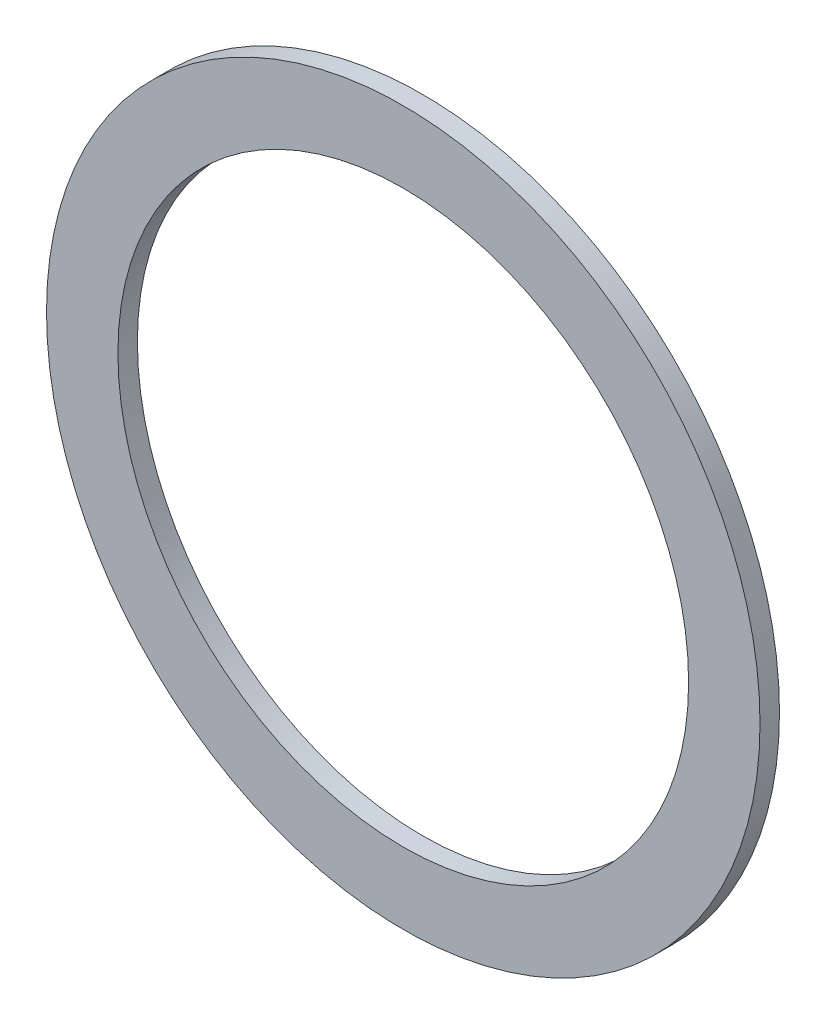
SolidWorks part; units mm, degrees
material "6061-T6 (SS)"
ref_plane "Front" through (0, 0, 0) normal (0, 0, 1) x (1, 0, 0)
ref_plane "Top" through (0, 0, 0) normal (0, 1, 0) x (1, 0, 0)
ref_plane "Right" through (0, 0, 0) normal (1, 0, 0) x (0, 0, -1)
sketch "Sketch1" plane through (0, 0, 0) normal (0, 0, 1) x (1, 0, 0)
  circle A0 centre (0, 0) radius 27.9146
  circle A1 centre (0, 0) radius 34.8996
  dimension "D1" = 69.7992
  dimension "D2" = 6.985
extrude "Boss-Extrude1" add sketch "Sketch1" along normal blind 1.905
